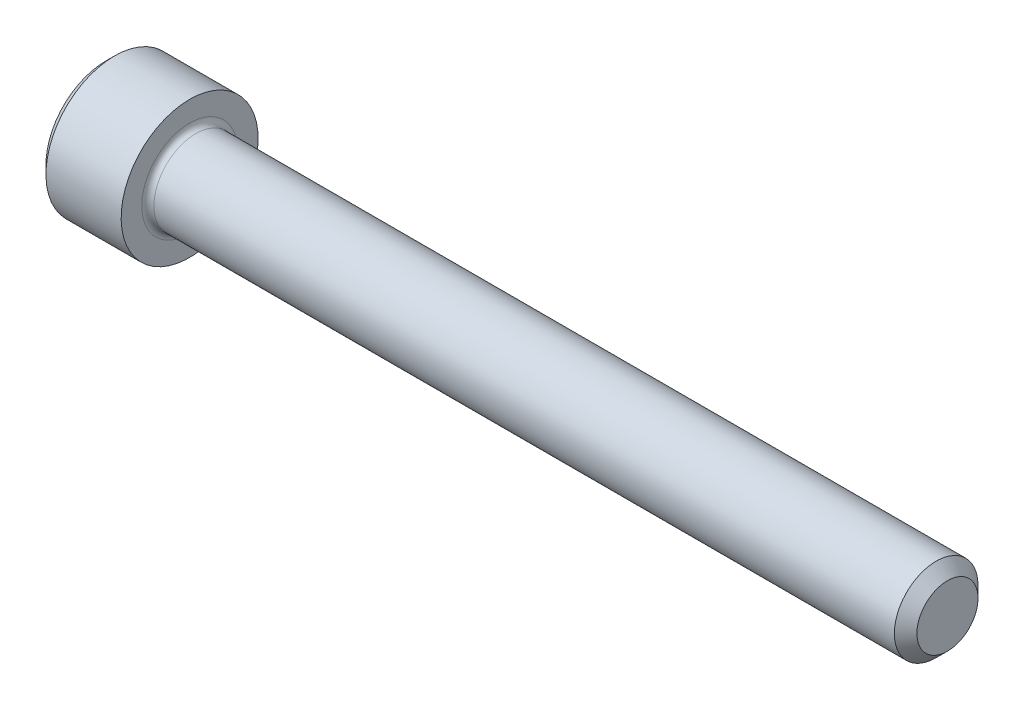
SolidWorks part; units mm, degrees
material "Alloy Steel"
ref_plane "Plane1" through (0, 0, 0) normal (0, 0, 1) x (1, 0, 0)
ref_plane "Plane2" through (0, 0, 0) normal (0, 1, 0) x (1, 0, 0)
ref_plane "Plane3" through (0, 0, 0) normal (1, 0, 0) x (0, 0, -1)
sketch "Sketch1" plane through (0, 0, 0) normal (0, 0, 1) x (1, 0, 0)
  line L0 (-3.5052, 0) -> (-3.5052, 2.8702)
  line L1 (-3.5052, 2.8702) -> (0, 2.8702)
  line L2 (0, 2.8702) -> (0, 1.7526)
  line L3 (0, 1.7526) -> (31.75, 1.7526)
  line L4 (31.75, 1.7526) -> (31.75, 0)
  line L5 (31.75, 0) -> (-3.5052, 0)
  line L7 (-3.5052, 0) -> (31.75, 0) construction
  dimension "D1" = 5.7404
  dimension "D2" = 3.5052
  dimension "D3" = 3.5052
  dimension "D4" = 35.2552
revolve "Base-Revolve" add sketch "Sketch1" angle 360 about L5
sketch "Sketch2" plane through (0, 0, 0) normal (0, 0, 1) x (1, 0, 0)
  line L0 (-3.5052, 1.3843) -> (-1.8796, 1.3843)
  line L1 (-1.8796, 1.3843) -> (-1.0804, 0)
  line L2 (-3.5052, 0) -> (31.75, 0) construction
  line L3 (-1.0804, 0) -> (-3.5052, 0)
  line L4 (-3.5052, 0) -> (-3.5052, 1.3843)
  line L8 (-3.5052, 2.8702) -> (-3.5052, -2.8702) construction
  dimension "D1" = 1.3843
  dimension "D2" = 60
  dimension "D3" = 2.4248
revolve "Hex-PreBroach" cut sketch "Sketch2" angle 360 about axis through (31.75, 0, 0) along (-1, 0, 0)
sketch "Sketch3" plane through (-3.5052, 0, 0) normal (-1, 0, 0) x (0, 0.5, 0.866)
  line L0 (0.7992, 1.3843) -> (-0.7992, 1.3843)
  line L1 (-0.7992, 1.3843) -> (-1.5985, 0)
  line L2 (0.7992, 1.3843) -> (1.5985, 0)
  line L3 (0.7992, -1.3843) -> (1.5985, 0)
  line L4 (0.7992, -1.3843) -> (-0.7992, -1.3843)
  line L5 (-0.7992, -1.3843) -> (-1.5985, 0)
  dimension "D1" = 1.3843
  dimension "D2" = 1.3843
  dimension "D3" = 2.7686
  dimension "Hex_size" = 2.7686
extrude "Hex" cut sketch "Sketch3" against normal blind 1.6256
fillet "Fillet1" radius 0.254 1 edges at (0, 1.7526, 0)
chamfer "Chamfer1" distance 0.4724 angle 45 1 edges at (31.75, 1.7526, 0)
chamfer "Chamfer2" distance 0.3556 angle 45 1 edges at (-3.5052, 2.8702, 0)
